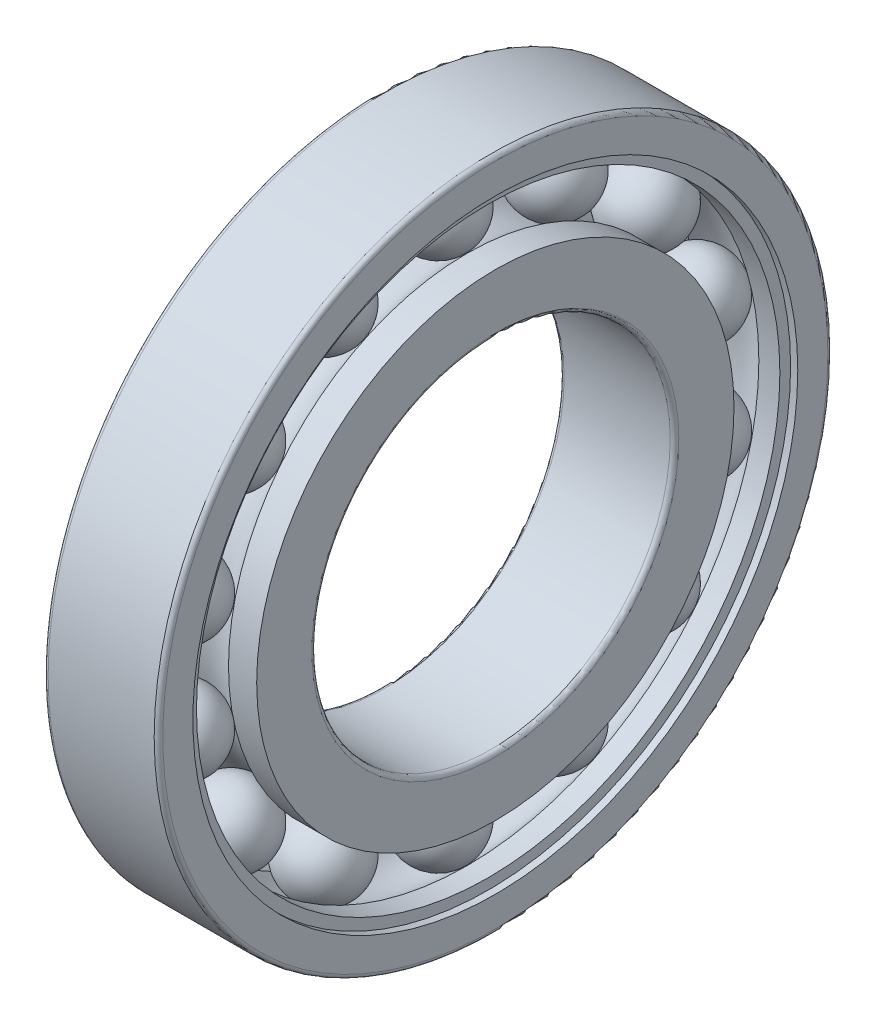
SolidWorks part; units mm, degrees
ref_plane "Front Plane" through (0, 0, 0) normal (0, 0, 1) x (1, 0, 0)
ref_plane "Top Plane" through (0, 0, 0) normal (0, 1, 0) x (1, 0, 0)
ref_plane "Right Plane" through (0, 0, 0) normal (1, 0, 0) x (0, 0, -1)
sketch "Sketch1" plane through (0, 0, 0) normal (0, 0, 1) x (1, 0, 0)
  line L0 (0, 0) -> (0, 21.925) construction
  line L9 (0, 0) -> (12.2235, 0) construction
  line L10 (-2.3431, 20.35) -> (-2.3431, 16.65) construction
  line L11 (4, 23.5) -> (-4, 23.5)
  line L12 (4, 23.5) -> (4, 20.35)
  line L13 (4, 20.35) -> (-4, 20.35)
  line L14 (-4, 23.5) -> (-4, 20.35)
  line L15 (4, 23.5) -> (-4, 20.35) construction
  line L16 (4, 20.35) -> (-4, 23.5) construction
  line L17 (4, 16.65) -> (-4, 16.65)
  line L18 (4, 16.65) -> (4, 12.5)
  line L19 (4, 12.5) -> (-4, 12.5)
  line L20 (-4, 16.65) -> (-4, 12.5)
  line L21 (4, 16.65) -> (-4, 12.5) construction
  line L22 (4, 12.5) -> (-4, 16.65) construction
  line L23 (-2.3431, 18.5) -> (0, 18.5) construction
  circle A0 centre (0, 18.5) radius 2.75
  point P7 (0, 14.575)
  dimension "D6" = 5.5
  dimension "D1" = 12.5
  dimension "D2" = 16.65
  dimension "D3" = 20.35
  dimension "D4" = 23.5
  dimension "D5" = 8
revolve "Revolve1" add sketch "Sketch1" angle 360 about L9
sketch "Sketch2" plane through (4, 0, 0) normal (1, 0, 0) x (0, 0, -1)
  circle A0 centre (0, 0) radius 21.1
  circle A1 centre (0, 0) radius 20.35 construction
  circle A2 centre (0, 0) radius 20.35
  dimension "D1" = 42.2
extrude "Cut-Extrude1" cut sketch "Sketch2" against normal blind 0.5
mirror "Mirror1" about plane through (0, 0, 0) normal (1, 0, 0) of "Cut-Extrude1"
fillet "Fillet1" radius 0.3 2 edges at (-4, 0, 23.5) (4, 0, 23.5)
fillet "Fillet2" radius 0.3 2 edges at (-4, 0, 12.5) (4, 0, 12.5)
sketch "Sketch3" plane through (0, 0, 0) normal (0, 0, 1) x (1, 0, 0)
  line L0 (-2.725, 18.5) -> (2.725, 18.5)
  arc A0 (2.725, 18.5) -> (-2.725, 18.5) centre (0, 18.5) ccw
  dimension "D1" = 5.45
  dimension "D2" = 18.5
revolve "Revolve2" add sketch "Sketch3" angle 360 about L0
pattern_circular "CirPattern4" count 14 over 360 about axis through (0, 0, 0) along (1, 0, 0) of bodies 105
